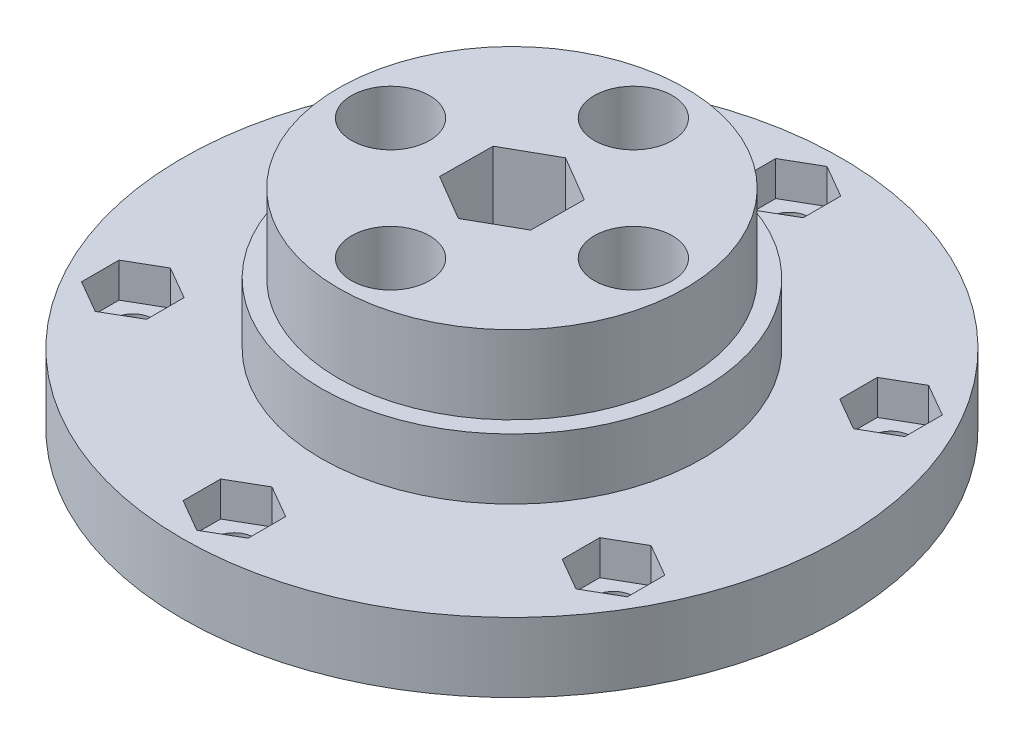
SolidWorks part; units mm, degrees
ref_plane "Спереди" through (0, 0, 0) normal (0, 0, 1) x (1, 0, 0)
ref_plane "Сверху" through (0, 0, 0) normal (0, 1, 0) x (1, 0, 0)
ref_plane "Справа" through (0, 0, 0) normal (1, 0, 0) x (0, 0, -1)
sketch "Эскиз1" plane through (0, 0, 0) normal (0, 1, 0) x (1, 0, 0)
  circle A0 centre (0, 0) radius 38
  dimension "D1" = 76
extrude "Бобышка-Вытянуть1" add sketch "Эскиз1" along normal blind 8
sketch "Эскиз2" plane through (0, 8, 0) normal (0, 1, 0) x (1, 0, 0)
  circle A0 centre (0, 0) radius 20
  dimension "D1" = 40
extrude "Бобышка-Вытянуть2" add sketch "Эскиз2" along normal blind 16
sketch "Эскиз7" plane through (0, 8, 0) normal (0, 1, 0) x (1, 0, 0)
  circle A0 centre (0, 0) radius 22
  dimension "D1" = 44
extrude "Бобышка-Вытянуть3" add sketch "Эскиз7" along normal blind 7
sketch "Эскиз3" plane through (0, 24, 0) normal (0, 1, 0) x (1, 0, 0)
  circle A0 centre (0, 14) radius 4.5
  circle A1 centre (14, 0) radius 4.5
  circle A2 centre (0, -14) radius 4.5
  circle A3 centre (-14, 0) radius 4.5
  circle A4 centre (0, 0) radius 3.25
  point P12 (0, 0)
  dimension "D2" = 9
  dimension "D4" = 6.5
  dimension "D1" = 14
  dimension "D3" = 4
extrude "Вырез-Вытянуть1" cut sketch "Эскиз3" against normal through all
sketch "Эскиз4" plane through (0, 24, 0) normal (0, 1, 0) x (1, 0, 0)
  line L1 (5.2713, -3.1091) -> (5.3282, 3.0105)
  line L2 (5.3282, 3.0105) -> (0.0569, 6.1196)
  line L3 (0.0569, 6.1196) -> (-5.2713, 3.1091)
  line L4 (-5.2713, 3.1091) -> (-5.3282, -3.0105)
  line L5 (-5.3282, -3.0105) -> (-0.0569, -6.1196)
  line L6 (-0.0569, -6.1196) -> (5.2713, -3.1091)
  circle A0 centre (0, 0) radius 5.3 construction
  dimension "D1" = 10.6
extrude "Вырез-Вытянуть2" cut sketch "Эскиз4" against normal blind 12
sketch "Эскиз5" plane through (0, 24, 0) normal (0, 1, 0) x (1, 0, 0)
  circle A1 centre (0, 32) radius 2.25
  circle A2 centre (27.7128, 16) radius 2.25
  circle A3 centre (27.7128, -16) radius 2.25
  circle A4 centre (0, -32) radius 2.25
  circle A5 centre (-27.7128, -16) radius 2.25
  circle A6 centre (-27.7128, 16) radius 2.25
  point P17 (0, 0)
  dimension "D1" = 4.5
  dimension "D3" = 6
  dimension "D2" = 32
extrude "Вырез-Вытянуть3" cut sketch "Эскиз5" against normal through all
sketch "Эскиз6" plane through (0, 8, 0) normal (0, 1, 0) x (1, 0, 0)
  line L0 (27.7128, 11.6699) -> (31.4628, 13.8349)
  line L1 (3.75, 29.8349) -> (3.75, 34.1651)
  line L2 (3.75, 34.1651) -> (0, 36.3301)
  line L3 (0, 36.3301) -> (-3.75, 34.1651)
  line L4 (-3.75, 34.1651) -> (-3.75, 29.8349)
  line L5 (-3.75, 29.8349) -> (0, 27.6699)
  line L6 (0, 27.6699) -> (3.75, 29.8349)
  line L7 (31.4628, 13.8349) -> (31.4628, 18.1651)
  line L8 (31.4628, 18.1651) -> (27.7128, 20.3301)
  line L9 (27.7128, 20.3301) -> (23.9628, 18.1651)
  line L10 (23.9628, 18.1651) -> (23.9628, 13.8349)
  line L11 (23.9628, 13.8349) -> (27.7128, 11.6699)
  line L12 (23.9628, -18.1651) -> (27.7128, -20.3301)
  line L13 (27.7128, -20.3301) -> (31.4628, -18.1651)
  line L14 (31.4628, -18.1651) -> (31.4628, -13.8349)
  line L15 (31.4628, -13.8349) -> (27.7128, -11.6699)
  line L16 (27.7128, -11.6699) -> (23.9628, -13.8349)
  line L17 (23.9628, -13.8349) -> (23.9628, -18.1651)
  line L18 (-3.75, -29.8349) -> (-3.75, -34.1651)
  line L19 (-3.75, -34.1651) -> (0, -36.3301)
  line L20 (0, -36.3301) -> (3.75, -34.1651)
  line L21 (3.75, -34.1651) -> (3.75, -29.8349)
  line L22 (3.75, -29.8349) -> (0, -27.6699)
  line L23 (0, -27.6699) -> (-3.75, -29.8349)
  line L24 (-27.7128, -11.6699) -> (-31.4628, -13.8349)
  line L25 (-31.4628, -13.8349) -> (-31.4628, -18.1651)
  line L26 (-31.4628, -18.1651) -> (-27.7128, -20.3301)
  line L27 (-27.7128, -20.3301) -> (-23.9628, -18.1651)
  line L28 (-23.9628, -18.1651) -> (-23.9628, -13.8349)
  line L29 (-23.9628, -13.8349) -> (-27.7128, -11.6699)
  line L30 (-23.9628, 18.1651) -> (-27.7128, 20.3301)
  line L31 (-27.7128, 20.3301) -> (-31.4628, 18.1651)
  line L32 (-31.4628, 18.1651) -> (-31.4628, 13.8349)
  line L33 (-31.4628, 13.8349) -> (-27.7128, 11.6699)
  line L34 (-27.7128, 11.6699) -> (-23.9628, 13.8349)
  line L35 (-23.9628, 13.8349) -> (-23.9628, 18.1651)
  circle A0 centre (0, 32) radius 3.75 construction
  circle A1 centre (27.7128, 16) radius 3.75 construction
  circle A2 centre (27.7128, -16) radius 3.75 construction
  circle A3 centre (0, -32) radius 3.75 construction
  circle A4 centre (-27.7128, -16) radius 3.75 construction
  circle A5 centre (-27.7128, 16) radius 3.75 construction
  point P52 (0, 0)
  dimension "D1" = 7.5
  dimension "D2" = 6
extrude "Вырез-Вытянуть4" cut sketch "Эскиз6" against normal blind 4
chamfer "Фаска1" [suppressed] distance 0.5 angle 45
